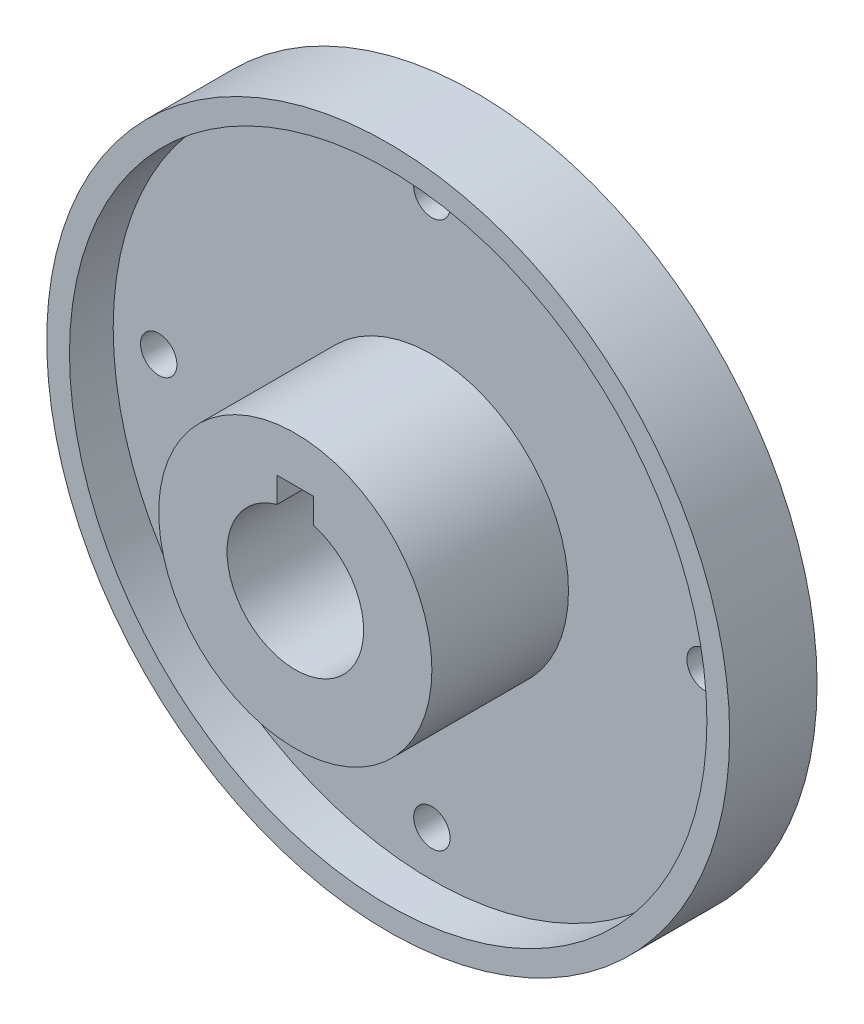
SolidWorks part; units mm, degrees
ref_plane "Front Plane" through (0, 0, 0) normal (0, 0, 1) x (1, 0, 0)
ref_plane "Top Plane" through (0, 0, 0) normal (0, 1, 0) x (1, 0, 0)
ref_plane "Right Plane" through (0, 0, 0) normal (1, 0, 0) x (0, 0, -1)
sketch "Sketch1" plane through (0, 0, 0) normal (0, 0, 1) x (1, 0, 0)
  circle A0 centre (0, 0) radius 75
  dimension "D1" = 150
extrude "Boss-Extrude3" add sketch "Sketch1" along normal blind 19.2
sketch "Sketch3" plane through (0, 0, 19.2) normal (0, 0, 1) x (1, 0, 0)
  circle A0 centre (0, 0) radius 70
  dimension "D1" = 140
extrude "Cut-Extrude1" cut sketch "Sketch3" against normal blind 9.6
sketch "Sketch4" plane through (0, 0, 9.6) normal (0, 0, 1) x (1, 0, 0)
  circle A0 centre (0, 0) radius 30
  dimension "D1" = 60
extrude "Boss-Extrude4" add sketch "Sketch4" along normal blind 30
sketch "Sketch5" plane through (0, 0, 39.6) normal (0, 0, 1) x (1, 0, 0)
  circle A0 centre (0, 0) radius 15
  dimension "D1" = 30
extrude "Cut-Extrude2" cut sketch "Sketch5" against normal blind 57
sketch "Sketch6" plane through (0, 0, 9.6) normal (0, 0, 1) x (1, 0, 0)
  circle A0 centre (0, 60) radius 4
  circle A1 centre (60, 0) radius 4
  circle A2 centre (0, -60) radius 4
  circle A3 centre (-60, 0) radius 4
  dimension "D1" = 8
  dimension "D2" = 60
  dimension "D3" = 4
extrude "Cut-Extrude3" cut sketch "Sketch6" against normal blind 57
sketch "Sketch7" plane through (0, 0, 39.6) normal (0, 0, 1) x (1, 0, 0)
  line L1 (-4, 20) -> (4, 20)
  line L2 (-4, 20) -> (-4, 10)
  line L3 (-4, 10) -> (4, 10)
  line L4 (4, 20) -> (4, 10)
  line L5 (-4, 20) -> (4, 10) construction
  line L6 (-4, 10) -> (4, 20) construction
  circle A0 centre (0, 0) radius 15 construction
  point P0 (0, 15)
  dimension "D1" = 10
  dimension "D2" = 8
extrude "Cut-Extrude4" cut sketch "Sketch7" against normal blind 30
